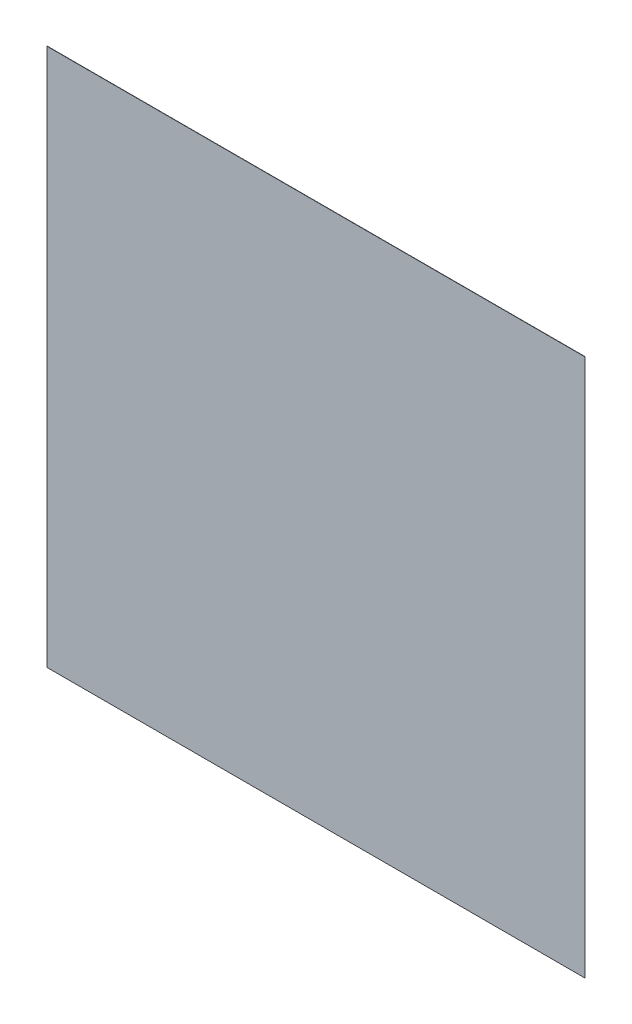
SolidWorks part; units mm, degrees
ref_plane "Front Plane" through (0, 0, 0) normal (0, 0, 1) x (1, 0, 0)
ref_plane "Top Plane" through (0, 0, 0) normal (0, 1, 0) x (1, 0, 0)
ref_plane "Right Plane" through (0, 0, 0) normal (1, 0, 0) x (0, 0, -1)
sketch "Sketch1" plane through (0, 0, 0) normal (0, 0, 1) x (1, 0, 0)
  line L1 (-15, -15) -> (15, -15)
  line L2 (-15, -15) -> (-15, 15)
  line L3 (-15, 15) -> (15, 15)
  line L4 (15, -15) -> (15, 15)
  line L5 (0, 15) -> (0, -15) construction
  line L6 (-15, 0) -> (15, 0) construction
  point P1 (0, 0)
  dimension "D1" = 30
  dimension "D2" = 30
extrude "Boss-Extrude1" add sketch "Sketch1" along normal blind 0.015
